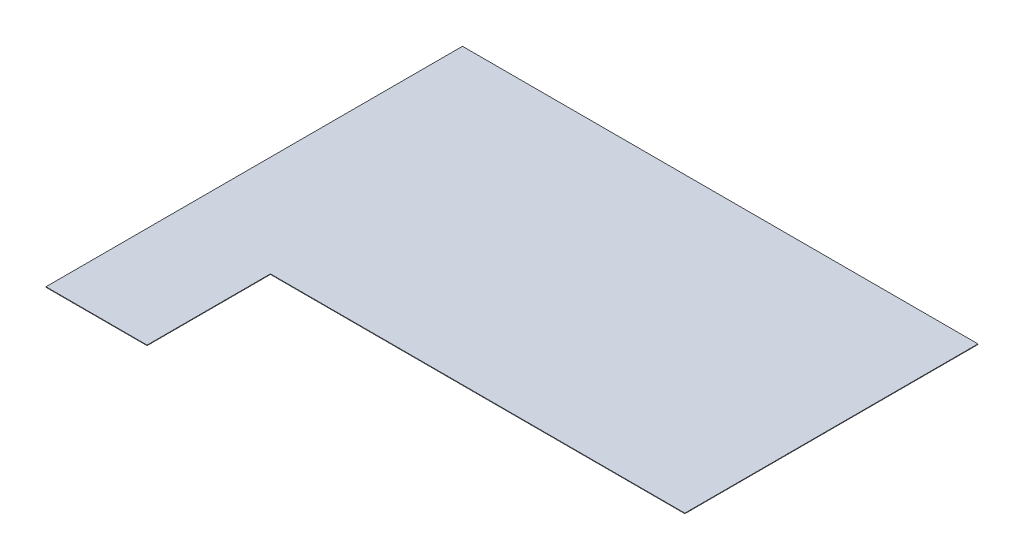
SolidWorks part; units mm, degrees
material "Резина"
ref_plane "Спереди" through (0, 0, 0) normal (0, 0, 1) x (1, 0, 0)
ref_plane "Сверху" through (0, 0, 0) normal (0, 1, 0) x (1, 0, 0)
ref_plane "Справа" through (0, 0, 0) normal (1, 0, 0) x (0, 0, -1)
sketch "Эскиз1" plane through (0, 0, 0) normal (0, 1, 0) x (1, 0, 0)
  line L0 (-4100, -4120.283) -> (-4100, -2900) construction
  line L1 (-5100, -4120.283) -> (-4100, -4120.283) construction
  line L2 (-5100, 0) -> (-5100, -4120.283) construction
  line L3 (0, 0) -> (-5100, 0) construction
  line L4 (0, -2900) -> (0, 0) construction
  line L5 (-4100, -2900) -> (0, -2900) construction
  line L6 (-4100, -4120.283) -> (-4100, -2900)
  line L7 (-5100, -4120.283) -> (-4100, -4120.283)
  line L8 (-5100, 0) -> (-5100, -4120.283)
  line L9 (0, 0) -> (-5100, 0)
  line L10 (0, -2900) -> (0, 0)
  line L11 (-4100, -2900) -> (0, -2900)
extrude "Бобышка-Вытянуть1" add sketch "Эскиз1" along normal blind 5
